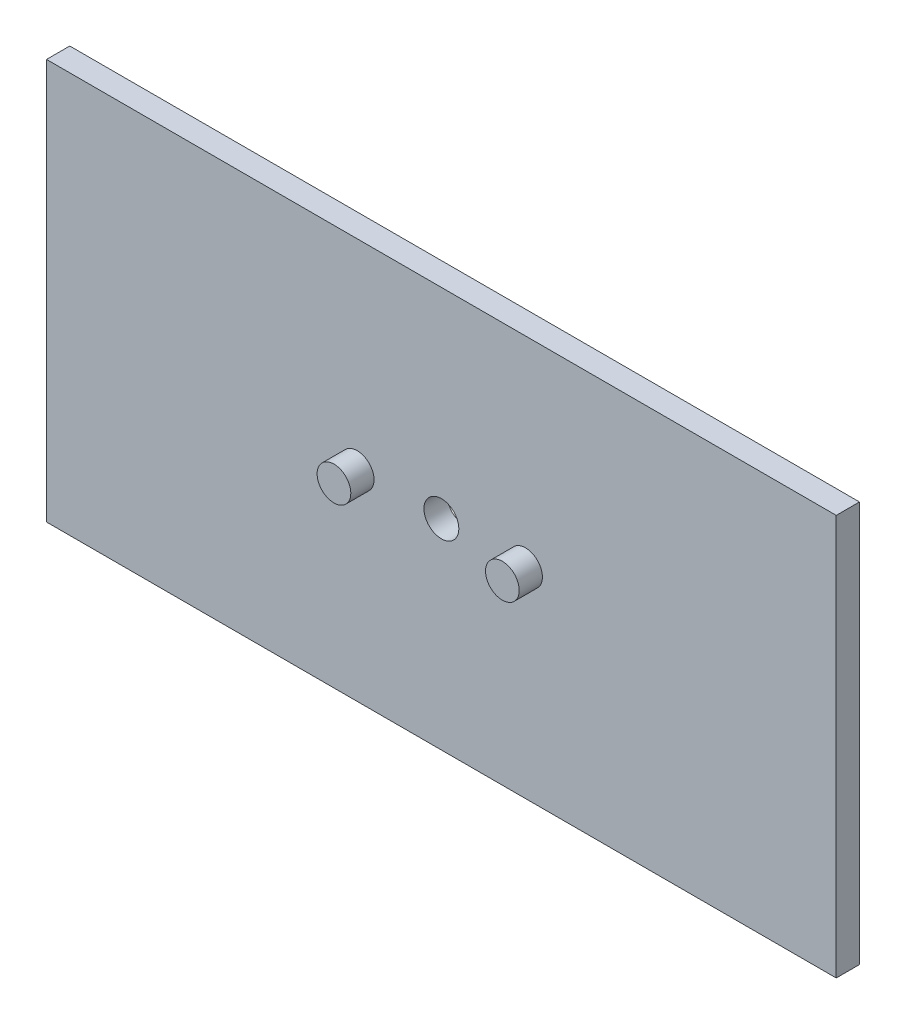
SolidWorks part; units mm, degrees
ref_plane "Front Plane" through (0, 0, 0) normal (0, 0, 1) x (1, 0, 0)
ref_plane "Top Plane" through (0, 0, 0) normal (0, 1, 0) x (1, 0, 0)
ref_plane "Right Plane" through (0, 0, 0) normal (1, 0, 0) x (0, 0, -1)
sketch "Sketch1" plane through (0, 0, 0) normal (0, 0, 1) x (1, 0, 0)
  line L1 (-34, -17.25) -> (34, -17.25)
  line L2 (-34, -17.25) -> (-34, 17.25)
  line L3 (-34, 17.25) -> (34, 17.25)
  line L4 (34, -17.25) -> (34, 17.25)
  line L5 (-34, -17.25) -> (34, 17.25) construction
  line L6 (-34, 17.25) -> (34, -17.25) construction
  point P0 (0, 0)
  dimension "D1" = 34.5
  dimension "D2" = 68
extrude "Boss-Extrude1" add sketch "Sketch1" along normal blind 2
sketch "Sketch2" plane through (0, 0, 2) normal (0, 0, 1) x (1, 0, 0)
  circle A0 centre (-7.25, 0) radius 1.45
  circle A1 centre (7.25, 0) radius 1.45
  dimension "D3" = 2.9
  dimension "D4" = 2.9
  dimension "D1" = 14.5
  dimension "D2" = 7.25
extrude "Boss-Extrude2" add sketch "Sketch2" along normal blind 2
sketch "Sketch3" plane through (0, 0, 2) normal (0, 0, 1) x (1, 0, 0)
  circle A0 centre (0, 0) radius 1.5
  dimension "D1" = 3
extrude "Cut-Extrude1" cut sketch "Sketch3" against normal through all
